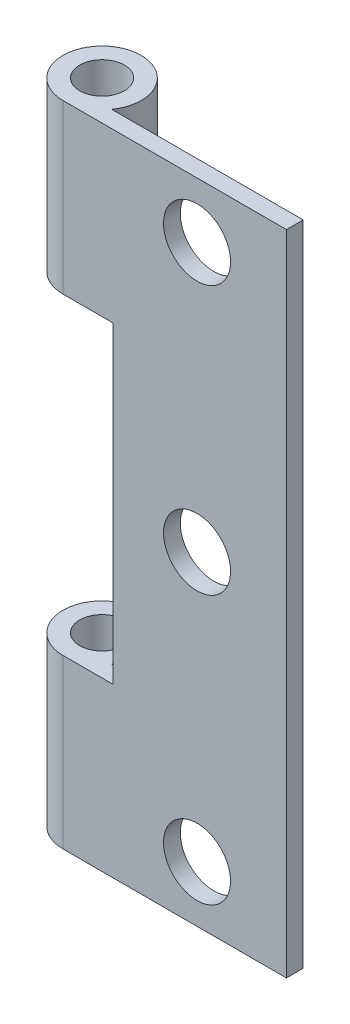
SolidWorks part; units mm, degrees
material "Plain Carbon Steel"
ref_plane "Front Plane" through (0, 0, 0) normal (0, 0, 1) x (1, 0, 0)
ref_plane "Top Plane" through (0, 0, 0) normal (0, 1, 0) x (1, 0, 0)
ref_plane "Right Plane" through (0, 0, 0) normal (1, 0, 0) x (0, 0, -1)
sketch "Sketch1" plane through (0, 0, 0) normal (0, 0, 1) x (1, 0, 0)
  line L1 (-7.9375, -23.0188) -> (7.9375, -23.0188)
  line L2 (-7.9375, -23.0188) -> (-7.9375, 23.0188)
  line L3 (-7.9375, 23.0188) -> (7.9375, 23.0188)
  line L4 (7.9375, -23.0188) -> (7.9375, 23.0188)
  line L5 (-7.9375, -23.0188) -> (7.9375, 23.0188) construction
  line L6 (-7.9375, 23.0188) -> (7.9375, -23.0188) construction
  point P0 (0, 0)
  dimension "D1" = 46.0375
  dimension "D2" = 15.875
extrude "Boss-Extrude1" add sketch "Sketch1" along normal mid plane 1.1906
sketch "Sketch2" plane through (0, 0, 0) normal (0, 1, 0) x (1, 0, 0)
  circle A0 centre (-7.9375, 2.1828) radius 2.7781
  circle A1 centre (-7.9375, 2.1828) radius 1.5875
  dimension "D1" = 5.5562
  dimension "D2" = 3.175
extrude "Boss-Extrude2" add sketch "Sketch2" along normal mid plane 46.0375
sketch "Sketch3" plane through (0, 0, 0) normal (0, 0, 1) x (1, 0, 0)
  line L0 (-10.7156, 23.0188) -> (-10.7156, -23.0188) construction
  line L1 (-10.7156, 11.1125) -> (-4.3656, 11.1125)
  line L2 (-10.7156, 11.1125) -> (-10.7156, -11.1125)
  line L3 (-10.7156, -11.1125) -> (-4.3656, -11.1125)
  line L4 (-4.3656, 11.1125) -> (-4.3656, -11.1125)
  line L5 (-10.7156, 11.1125) -> (-4.3656, -11.1125) construction
  line L6 (-10.7156, -11.1125) -> (-4.3656, 11.1125) construction
  point P0 (-7.5406, 0)
  dimension "D1" = 6.35
  dimension "D2" = 22.225
extrude "Cut-Extrude1" cut sketch "Sketch3" against normal through all both and the other way through all
hole_wizard "3/16 (0.1875) Diameter Hole1" positions "Sketch4" profile "Sketch5" hole size "3/16" standard "ANSI Inch" end condition through all
sketch "Sketch4" plane through (0, 0, -0.5953) normal (0, 0, -1) x (-1, 0, 0)
  line L0 (-1.5875, -19.05) -> (-1.5875, 19.05) construction
  line L2 (5.6576, -23.0188) -> (-7.9375, -23.0188) construction
  line L3 (-7.9375, 23.0188) -> (5.6576, 23.0188) construction
  line L4 (-7.9375, -23.0188) -> (-7.9375, 23.0188) construction
  point P0 (-1.5875, -19.05)
  point P2 (-1.5875, 0)
  point P4 (-1.5875, 19.05)
  dimension "D1" = 3.9688
  dimension "D2" = 3.9688
  dimension "D3" = 6.35
sketch "Sketch5" plane through (1.5875, -19.05, -0.5953) normal (1, 0, 0) x (0, 1, 0)
  line L0 (0, 0) -> (0, 1.1906)
  line L1 (0, 1.1906) -> (2.3812, 1.1906)
  line L2 (2.3812, 1.1906) -> (2.3812, 0)
  line L5 (2.3812, 0) -> (0, 0)
  line L11 (0, -6.35) -> (0, 107.95) construction
  dimension "Thru Hole Dia." = 4.7625
  dimension "Thru Hole Depth" = 1.1906
